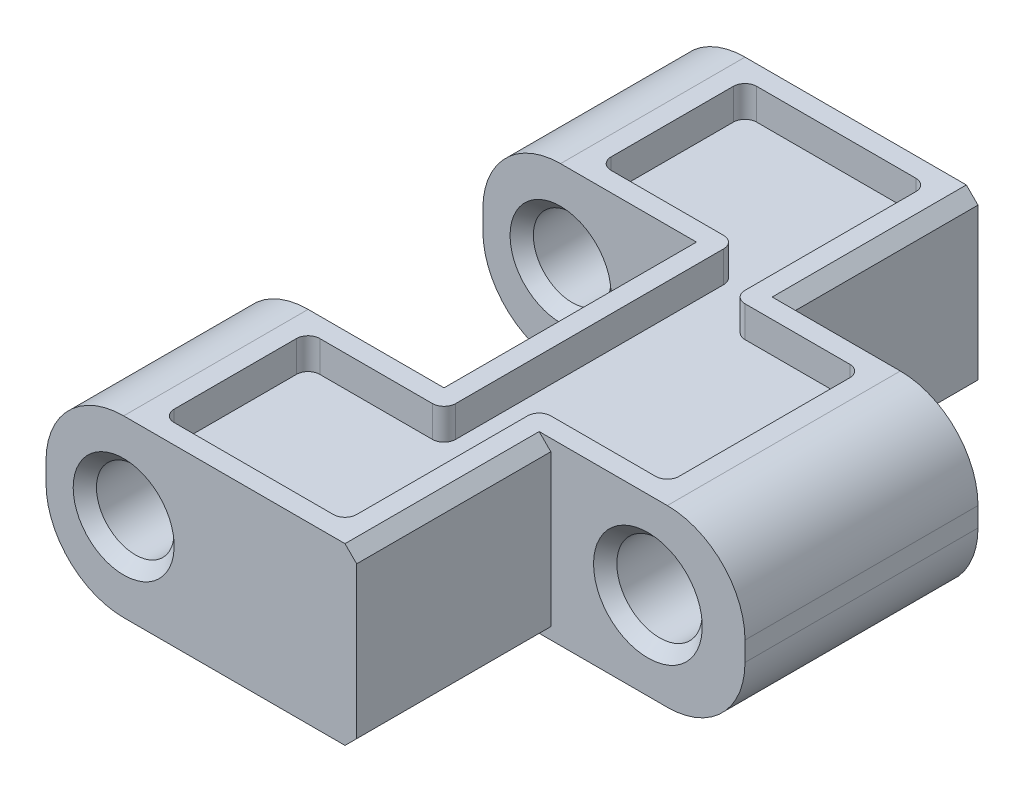
SolidWorks part; units mm, degrees
ref_plane "Ebene vorne" through (0, 0, 0) normal (0, 0, 1) x (1, 0, 0)
ref_plane "Ebene oben" through (0, 0, 0) normal (0, 1, 0) x (1, 0, 0)
ref_plane "Ebene rechts" through (0, 0, 0) normal (1, 0, 0) x (0, 0, -1)
sketch "Skizze1" plane through (0, 0, 0) normal (0, 1, 0) x (1, 0, 0)
  line L0 (0, 0) -> (13, 0) construction
  line L1 (5.5, 3.25) -> (5.5, -3.25)
  line L2 (5.5, -3.25) -> (0, -3.25)
  line L3 (0, -3.25) -> (0, -8)
  line L4 (0, -8) -> (8, -8)
  line L5 (8, -8) -> (8, -3)
  line L6 (8, -3) -> (13, -3)
  line L7 (13, -3) -> (13, 3)
  line L8 (8, 3) -> (13, 3)
  line L9 (8, 8) -> (8, 3)
  line L10 (0, 8) -> (8, 8)
  line L11 (0, 3.25) -> (0, 8)
  line L12 (5.5, 3.25) -> (0, 3.25)
  point P16 (5.5, 0)
  dimension "D1" = 13
  dimension "D2" = 5
  dimension "D3" = 5.5
  dimension "D4" = 16
  dimension "D5" = 6
  dimension "D6" = 6.5
extrude "Grundkörper" add sketch "Skizze1" along normal blind 4.5
sketch "Skizze2" plane through (0, 0, 0) normal (0, 0, 1) x (1, 0, 0)
  line L0 (0, 2.25) -> (2, 2.25) construction
  line L1 (0, 4.5) -> (0, 0) construction
  line L2 (2, 2.25) -> (10.5, 2.25) construction
  line L3 (10.5, 2.25) -> (13, 2.25) construction
  line L4 (13, 4.5) -> (13, 0) construction
  circle A0 centre (2, 2.25) radius 1
  circle A1 centre (10.5, 2.25) radius 1.1
  dimension "D3" = 2.2
  dimension "D4" = 2
  dimension "D1" = 2.5
  dimension "D2" = 2
extrude "Achsbohhrungen" cut sketch "Skizze2" against normal through all and the other way through all
sketch "Skizze3" plane through (0, 0, 0) normal (0, -1, 0) x (1, 0, 0)
  line L1 (5.5, 3.25) -> (7.5, 3.25)
  line L2 (5.5, 3.25) -> (5.5, -3.25)
  line L3 (5.5, -3.25) -> (7.5, -3.25)
  line L4 (7.5, 3.25) -> (7.5, -3.25)
  dimension "D1" = 2
extrude "Ausschnitt Zahn" cut sketch "Skizze3" against normal offset from surface (3 mm away) 1.5 up to face at (5.75, 4.5, 0)
sketch "Skizze4" plane through (0, 4.5, 0) normal (0, 1, 0) x (1, 0, 0)
  line L0 (5.5, -3.25) -> (0, -3.25) construction
  line L1 (5, -3.25) -> (6, -3.25)
  line L2 (4, -4.25) -> (4, -7)
  line L3 (5, -8) -> (6, -8)
  line L4 (6, -3.25) -> (6, -8)
  line L5 (0, -8) -> (8, -8) construction
  line L6 (8, -8) -> (8, -3) construction
  line L7 (0, -3.25) -> (0, -8) construction
  arc A0 (5, -8) -> (4, -7) centre (5, -7) cw
  arc A1 (4, -4.25) -> (5, -3.25) centre (5, -4.25) cw
  point P16 (4, -3.25)
  dimension "D3" = 1
  dimension "D1" = 2
  dimension "D2" = 4
ref_plane "Ebene2" through (0, 6.5, 0) normal (0, 1, 0) x (1, 0, 0)
sketch "Skizze5" plane through (0, 6.5, 0) normal (0, 1, 0) x (1, 0, 0)
  line L0 (6, -3.25) -> (6, -8) construction
  line L1 (6.5, -4.625) -> (6.3, -4.625)
  line L2 (6.5, -4.625) -> (6.5, -6.625)
  line L3 (6.5, -6.625) -> (6.3, -6.625)
  line L4 (6, -4.925) -> (6, -6.325)
  line L5 (4, -4.25) -> (4, -7) construction
  line L6 (6, -5.625) -> (6.5, -5.625) construction
  arc A0 (6.3, -6.625) -> (6, -6.325) centre (6.3, -6.325) cw
  arc A1 (6, -4.925) -> (6.3, -4.625) centre (6.3, -4.925) cw
  dimension "D4" = 0.3
  dimension "D1" = 0.5
  dimension "D2" = 2
  dimension "D3" = 2
loft "LaufKralle" [suppressed] add profiles "Skizze4", "Skizze5"
fillet "Verrundung7" [suppressed] radius 0.5
mirror "Spiegeln1" [suppressed] about plane through (0, 0, 0) normal (0, 0, 1)
fillet "Verrundung2" radius 2 6 edges at (0, 0, 5.625) (0, 0, -5.625) (0, 4.5, -5.625) (0, 4.5, 5.625) (13, 0, 0) (13, 4.5, 0)
chamfer "Fase1" distance 0.3 angle 45 4 edges at (8, 0, 5.5) (8, 0, -5.5) (8, 4.5, 5.5) (8, 4.5, -5.5)
chamfer "Fase2" distance 0.3 angle 45 6 edges at (11.6, 2.25, -3) (9.4, 2.25, 3) (1, 2.25, -3.25) (3, 2.25, 3.25) (3, 2.25, 8) (3, 2.25, -8)
ref_plane "Mitte" through (0, 0, 0) normal (0, 0, -1) x (-1, 0, 0)
sketch "Skizze6" plane through (0, 4.5, 0) normal (0, 1, 0) x (1, 0, 0)
  line L90 (10.5, -2.5) -> (10.5, 2.5)
  line L91 (7.2, -2.5) -> (10.5, -2.5)
  line L92 (10.5, 2.5) -> (7.2, 2.5)
  line L93 (7.2, 2.5) -> (7.2, 7.5)
  line L94 (7.2, -7.5) -> (7.2, -2.5)
  line L95 (2.5, -7.5) -> (7.2, -7.5)
  line L96 (2.5, -3.75) -> (2.5, -7.5)
  line L97 (6, -3.75) -> (2.5, -3.75)
  line L98 (6, 3.75) -> (6, -3.75)
  line L99 (2.5, 3.75) -> (6, 3.75)
  line L100 (2.5, 7.5) -> (2.5, 3.75)
  line L101 (7.2, 7.5) -> (2.5, 7.5)
  line L102 (10.5, -2.5) -> (10.5, 2.5)
  line L103 (7.2, -2.5) -> (10.5, -2.5)
  line L104 (10.5, 2.5) -> (7.2, 2.5)
  line L105 (7.2, 2.5) -> (7.2, 7.5)
  line L106 (7.2, -7.5) -> (7.2, -2.5)
  line L107 (2.5, -7.5) -> (7.2, -7.5)
  line L108 (2.5, -3.75) -> (2.5, -7.5)
  line L109 (6, -3.75) -> (2.5, -3.75)
  line L110 (6, 3.75) -> (6, -3.75)
  line L111 (2.5, 3.75) -> (6, 3.75)
  line L112 (2.5, 7.5) -> (2.5, 3.75)
  line L113 (7.2, 7.5) -> (2.5, 7.5)
  dimension "D1" = 0.5
extrude "MoosgummiVertiefung" cut sketch "Skizze6" against normal blind 0.8
fillet "Verrundung8" radius 0.3 12 edges at (7.2, 4.1, -2.5) (10.5, 4.1, -2.5) (10.5, 4.1, 2.5) (7.2, 4.1, 2.5) (7.2, 4.1, 7.5) (2.5, 4.1, 7.5) (2.5, 4.1, 3.75) (6, 4.1, 3.75) (6, 4.1, -3.75) (2.5, 4.1, -3.75) (2.5, 4.1, -7.5) (7.2, 4.1, -7.5)
equation "\"D2@Skizze2\"=\"D1@Skizze2\"-0.5"
